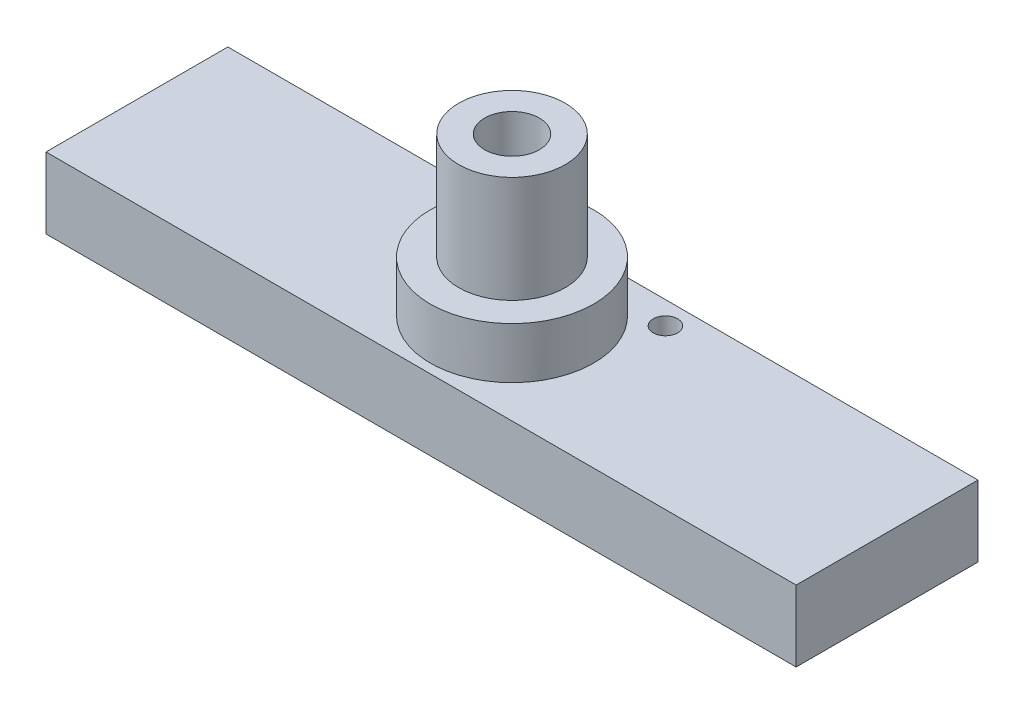
SolidWorks part; units mm, degrees
ref_plane "Front Plane" through (0, 0, 0) normal (0, 0, 1) x (1, 0, 0)
ref_plane "Top Plane" through (0, 0, 0) normal (0, 1, 0) x (1, 0, 0)
ref_plane "Right Plane" through (0, 0, 0) normal (1, 0, 0) x (0, 0, -1)
sketch "Sketch1" plane through (0, 0, 0) normal (0, 1, 0) x (1, 0, 0)
  line L1 (0, 0) -> (67.056, 0)
  line L2 (0, 0) -> (0, 16.256)
  line L3 (0, 16.256) -> (67.056, 16.256)
  line L4 (67.056, 0) -> (67.056, 16.256)
  dimension "D1" = 67.056
  dimension "D2" = 16.256
extrude "Boss-Extrude1" add sketch "Sketch1" along normal blind 6.35
sketch "Sketch2" plane through (0, 6.35, 0) normal (0, 1, 0) x (1, 0, 0)
  line L0 (0, 0) -> (67.056, 16.256) construction
  circle A0 centre (33.528, 8.128) radius 4.7625
  dimension "D1" = 9.525
extrude "Boss-Extrude2" add sketch "Sketch2" along normal blind 14.097
sketch "Sketch3" plane through (0, 20.447, 0) normal (0, 1, 0) x (1, 0, 0)
  circle A0 centre (33.528, 8.128) radius 2.4511
  dimension "D1" = 4.9022
extrude "Cut-Extrude1" cut sketch "Sketch3" against normal through all contours A0
sketch "Sketch4" plane through (0, 0, 0) normal (0, -1, 0) x (-1, 0, 0)
  line L0 (-67.056, 16.256) -> (0, 16.256) construction
  line L1 (-33.528, 14.224) -> (0, 14.224) construction
  line L2 (0, 16.256) -> (0, 0) construction
  line L3 (-33.528, 14.224) -> (-67.056, 14.224) construction
  line L4 (-67.056, 0) -> (-67.056, 16.256) construction
  line L5 (-41.148, 14.224) -> (-33.528, 14.224) construction
  line L6 (-33.528, 14.224) -> (-25.908, 14.224) construction
  circle A0 centre (-25.908, 14.224) radius 1.0922
  circle A1 centre (-41.148, 14.224) radius 1.0922
  dimension "D2" = 2.1844
  dimension "D3" = 2.1844
  dimension "D1" = 2.032
  dimension "D4" = 7.62
extrude "Cut-Extrude2" cut sketch "Sketch4" against normal up to next
sketch "Sketch6" plane through (0, 6.35, 0) normal (0, 1, 0) x (1, 0, 0)
  circle A0 centre (33.528, 8.128) radius 4.7625
  circle A1 centre (33.528, 8.128) radius 7.3025
  dimension "D1" = 2.54
extrude "Boss-Extrude3" add sketch "Sketch6" along normal blind 4.572
